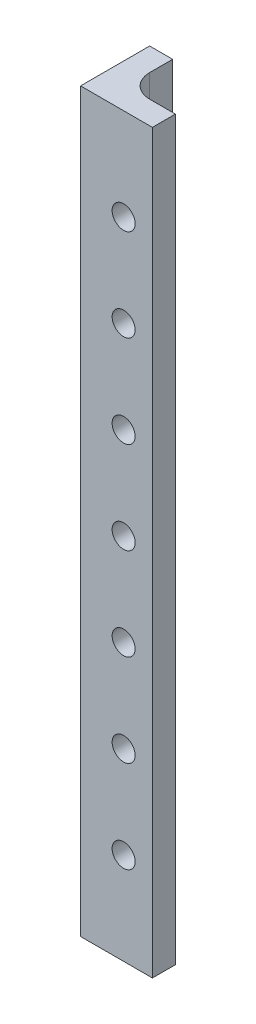
SolidWorks part; units mm, degrees
material "3003-O"
ref_plane "Front Plane" through (0, 0, 0) normal (0, 0, 1) x (1, 0, 0)
ref_plane "Top Plane" through (0, 0, 0) normal (0, 1, 0) x (1, 0, 0)
ref_plane "Right Plane" through (0, 0, 0) normal (1, 0, 0) x (0, 0, -1)
sketch "Sketch1" plane through (0, 0, 0) normal (0, 1, 0) x (1, 0, 0)
  line L0 (0, 0) -> (0, 19.05)
  line L1 (0, 19.05) -> (6.35, 19.05)
  line L2 (6.35, 19.05) -> (6.35, 6.35)
  line L3 (6.35, 6.35) -> (19.812, 6.35)
  line L4 (19.812, 6.35) -> (19.812, 0)
  line L5 (19.812, 0) -> (0, 0)
  dimension "D1" = 19.05
  dimension "D2" = 19.812
  dimension "D3" = 6.35
  dimension "D4" = 6.35
extrude "Boss-Extrude1" add sketch "Sketch1" against normal blind 203.2
fillet "Fillet1" radius 6.35 1 edges at (6.35, -101.6, -6.35)
sketch "Sketch2" plane through (0, 0, 0) normal (0, 0, 1) x (1, 0, 0)
  line L0 (19.812, -203.2) -> (19.812, 0) construction
  line L1 (0, 0) -> (19.812, 0) construction
  circle A0 centre (11.8745, -25.4) radius 3.175
  dimension "D1" = 6.35
  dimension "D2" = 7.9375
  dimension "D3" = 25.4
extrude "Cut-Extrude1" cut sketch "Sketch2" against normal through all
pattern_linear "LPattern1" count 7 spacing 25.4 along (0, -1, 0) of "Cut-Extrude1"
